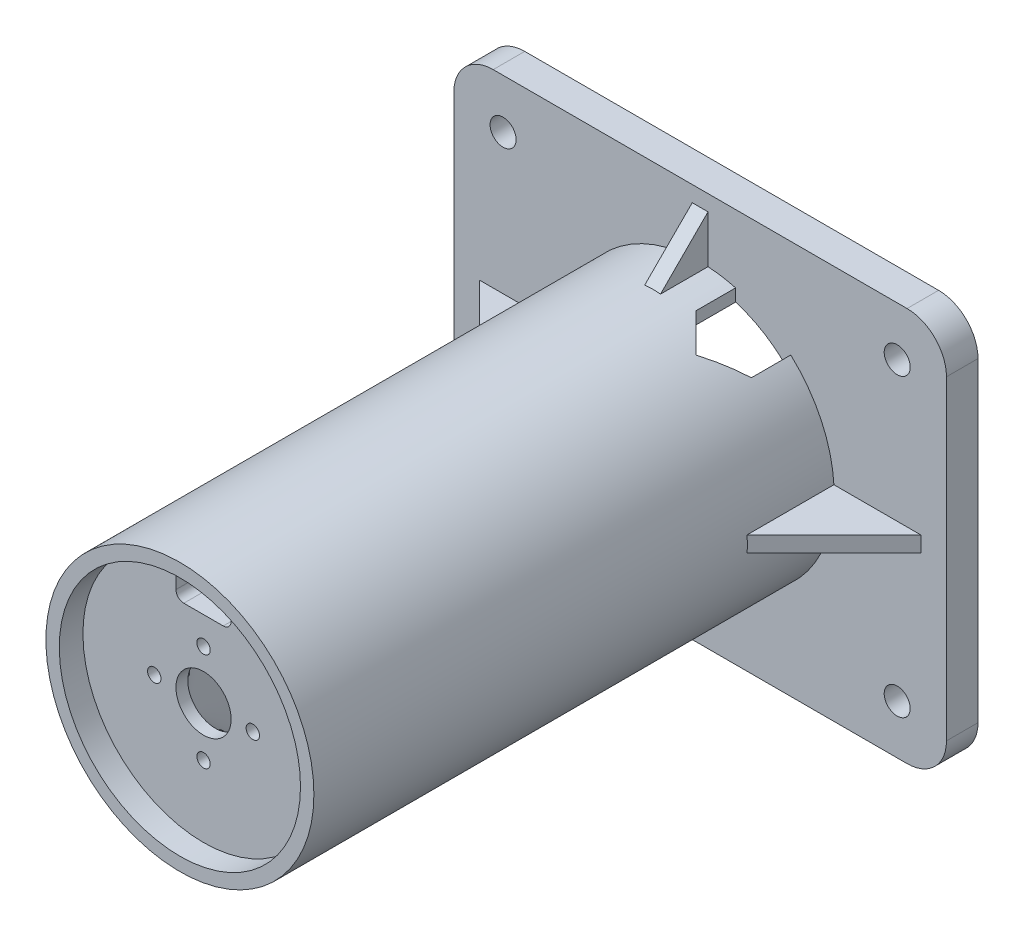
SolidWorks part; units mm, degrees
ref_plane "前视基准面" through (0, 0, 0) normal (0, 0, 1) x (1, 0, 0)
ref_plane "上视基准面" through (0, 0, 0) normal (0, 1, 0) x (1, 0, 0)
ref_plane "右视基准面" through (0, 0, 0) normal (1, 0, 0) x (0, 0, -1)
other "Configuration Table"
sketch "草图1" plane through (0, 0, 0) normal (0, 0, 1) x (1, 0, 0)
  line L0 (-52.5, -50) -> (52.5, -50)
  line L1 (62.5, -40) -> (62.5, 40)
  line L2 (52.5, 50) -> (-52.5, 50)
  line L3 (-62.5, 40) -> (-62.5, -40)
  arc A0 (-62.5, -40) -> (-52.5, -50) centre (-52.5, -40) ccw
  arc A1 (52.5, -50) -> (62.5, -40) centre (52.5, -40) ccw
  arc A2 (62.5, 40) -> (52.5, 50) centre (52.5, 40) ccw
  arc A3 (-52.5, 50) -> (-62.5, 40) centre (-52.5, 40) ccw
  circle A4 centre (0, 0) radius 31
extrude "Foot_125x100_R10_T8_open_D62" add sketch "草图1" along normal blind 8
ref_plane "Plane_z_8_1" through (0, 0, 8) normal (0, 0, 1) x (1, 0, 0)
sketch "草图2" plane through (0, 0, 8) normal (0, 0, 1) x (1, 0, 0)
  circle A0 centre (-50, -37.5) radius 3.3
  circle A1 centre (-50, 37.5) radius 3.3
  circle A2 centre (50, -37.5) radius 3.3
  circle A3 centre (50, 37.5) radius 3.3
extrude "M6_grid25_100x75" cut sketch "草图2" against normal blind 8
ref_plane "Plane_z_8_2" through (0, 0, 8) normal (0, 0, 1) x (1, 0, 0)
sketch "草图3" plane through (0, 0, 8) normal (0, 0, 1) x (1, 0, 0)
  circle A0 centre (0, 0) radius 34
  circle A1 centre (0, 0) radius 31
extrude "Hollow_column_OD68_ID62_toZ134" add sketch "草图3" along normal blind 126
sketch "草图4" plane through (0, 0, 0) normal (0, 1, 0) x (1, 0, 0)
  line L0 (7, -131) -> (31, -107)
  line L1 (31, -107) -> (34, -107)
  line L2 (34, -107) -> (34, -134)
  line L3 (34, -134) -> (7, -134)
  line L4 (7, -134) -> (7, -131)
  line L5 (0, 0) -> (0, -150) construction
revolve "Integral_motor_seat_45deg_internal_closure" add sketch "草图4" angle 360 about L5
ref_plane "Plane_z_134_4" through (0, 0, 134) normal (0, 0, 1) x (1, 0, 0)
sketch "草图5" plane through (0, 0, 134) normal (0, 0, 1) x (1, 0, 0)
  circle A0 centre (0, 0) radius 34
  circle A1 centre (0, 0) radius 30.6
extrude "Bottom_cap_wrap_OD68_ID61p2_H6" add sketch "草图5" along normal blind 6
ref_plane "Plane_x_-2_5" through (-2, 0, 0) normal (1, 0, 0) x (0, 0, -1)
sketch "草图6" plane through (-2, 0, 0) normal (1, 0, 0) x (0, 0, -1)
  line L0 (-8, -32) -> (-8, -46)
  line L1 (-8, -46) -> (-22, -32)
  line L2 (-22, -32) -> (-8, -32)
  line L3 (-8, 32) -> (-8, 46)
  line L4 (-8, 46) -> (-22, 32)
  line L5 (-22, 32) -> (-8, 32)
extrude "Straight_triangular_rib_T4_no_fillets_x" add sketch "草图6" along normal blind 4
ref_plane "Plane_y_-2_6" through (0, -2, 0) normal (0, 1, 0) x (1, 0, 0)
sketch "草图7" plane through (0, -2, 0) normal (0, 1, 0) x (1, 0, 0)
  line L0 (-32, -8) -> (-56, -8)
  line L1 (-56, -8) -> (-32, -32)
  line L2 (-32, -32) -> (-32, -8)
  line L3 (32, -8) -> (56, -8)
  line L4 (56, -8) -> (32, -32)
  line L5 (32, -32) -> (32, -8)
extrude "Straight_triangular_rib_T4_no_fillets_y" add sketch "草图7" along normal blind 4
ref_plane "Plane_z_134_7" through (0, 0, 134) normal (0, 0, 1) x (1, 0, 0)
sketch "草图8" plane through (0, 0, 134) normal (0, 0, 1) x (1, 0, 0)
  circle A0 centre (12.5, 0) radius 1.7
  circle A1 centre (0, 12.5) radius 1.7
  circle A2 centre (-12.5, 0) radius 1.7
  circle A3 centre (0, -12.5) radius 1.7
extrude "Stator_4xM3_PCD25_through_web" cut sketch "草图8" against normal blind 6
ref_plane "Plane_z_128_8" through (0, 0, 128) normal (0, 0, 1) x (1, 0, 0)
sketch "草图9" plane through (0, 0, 128) normal (0, 0, 1) x (1, 0, 0)
  circle A0 centre (12.5, 0) radius 3.3
  circle A1 centre (0, 12.5) radius 3.3
  circle A2 centre (-12.5, 0) radius 3.3
  circle A3 centre (0, -12.5) radius 3.3
extrude "Underside_bolt_and_driver_wells_D6p6" cut sketch "草图9" against normal blind 24
ref_plane "Plane_z_134_9" through (0, 0, 134) normal (0, 0, 1) x (1, 0, 0)
sketch "草图10" plane through (0, 0, 134) normal (0, 0, 1) x (1, 0, 0)
  line L0 (-5, 19.5) -> (5, 19.5)
  line L1 (7, 21.5) -> (7, 29.5)
  line L2 (5, 31.5) -> (-5, 31.5)
  line L3 (-7, 29.5) -> (-7, 21.5)
  arc A0 (-7, 21.5) -> (-5, 19.5) centre (-5, 21.5) ccw
  arc A1 (5, 19.5) -> (7, 21.5) centre (5, 21.5) ccw
  arc A2 (7, 29.5) -> (5, 31.5) centre (5, 29.5) ccw
  arc A3 (-5, 31.5) -> (-7, 29.5) centre (-5, 29.5) ccw
extrude "Inner_wall_wire_groove_W14_R2_depth40_no_external_bulge" cut sketch "草图10" against normal blind 40
ref_plane "Plane_y_40_10" through (0, 40, 0) normal (0, 1, 0) x (1, 0, 0)
sketch "草图11" plane through (0, 40, 0) normal (0, 1, 0) x (1, 0, 0)
  line L0 (9, -8) -> (23, -8)
  line L1 (23, -8) -> (23, -18)
  line L2 (23, -18) -> (16, -25)
  line L3 (16, -25) -> (9, -18)
  line L4 (9, -18) -> (9, -8)
extrude "Bottom_rear_offset_wire_exit_14x10_45deg_roof" cut sketch "草图11" against normal blind 25
